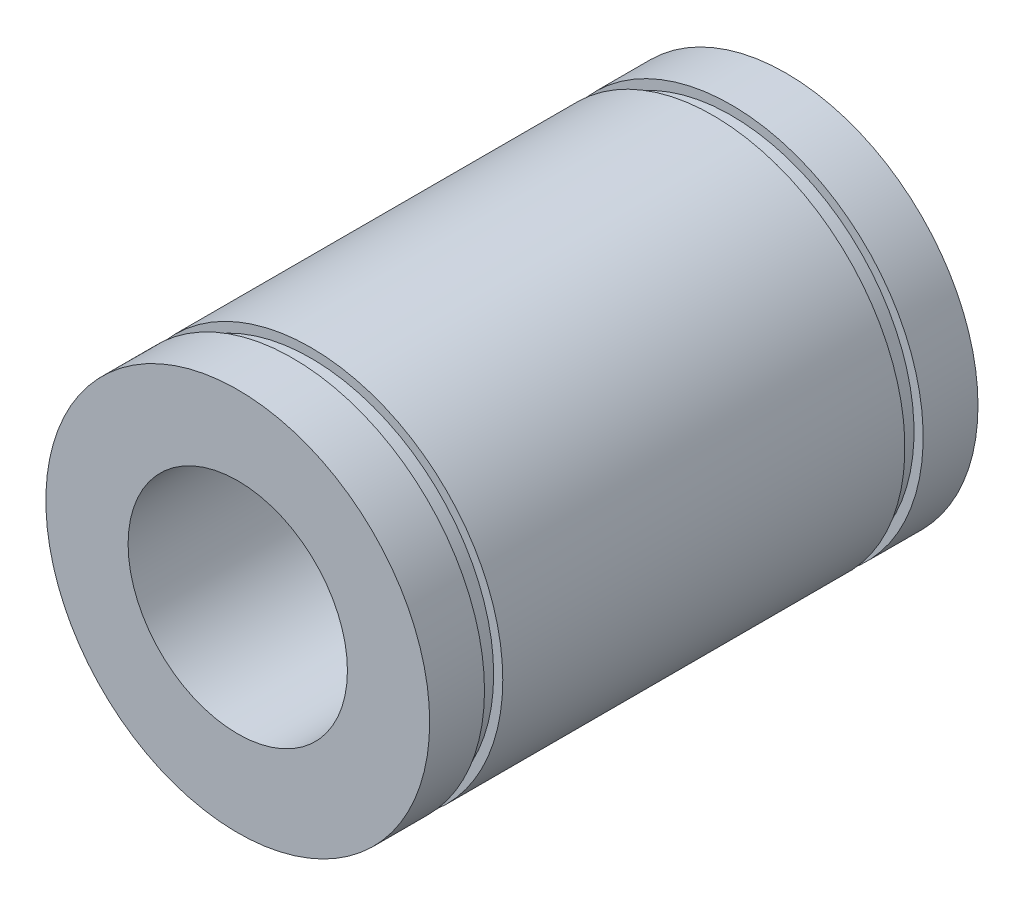
SolidWorks part; units mm, degrees
ref_plane "Front Plane" through (0, 0, 0) normal (0, 0, 1) x (1, 0, 0)
ref_plane "Top Plane" through (0, 0, 0) normal (0, 1, 0) x (1, 0, 0)
ref_plane "Right Plane" through (0, 0, 0) normal (1, 0, 0) x (0, 0, -1)
sketch "Sketch1" plane through (0, 0, 0) normal (0, 0, 1) x (1, 0, 0)
  circle A0 centre (0, 0) radius 10.5
  dimension "D1" = 21
extrude "Boss-Extrude1" add sketch "Sketch1" along normal blind 30
sketch "Sketch2" plane through (0, 0, 0) normal (0, 0, -1) x (-1, 0, 0)
  circle A0 centre (0, 0.1882) radius 6
  dimension "D1" = 12
extrude "Cut-Extrude1" cut sketch "Sketch2" against normal blind 30
sketch "Sketch3" plane through (0, 0, 0) normal (0, 0, -1) x (-1, 0, 0)
  circle A0 centre (0, 0) radius 10.5
  circle A1 centre (0, 0) radius 10
  dimension "D1" = 21
  dimension "D2" = 0.5
extrude "Cut-Extrude2" cut sketch "Sketch3" against normal blind 1 from offset 3 offset against normal yes
sketch "Sketch4" plane through (0, 0, 30) normal (0, 0, 1) x (1, 0, 0)
  circle A0 centre (0, 0) radius 10.5
  circle A1 centre (0, 0) radius 10
  dimension "D1" = 21
  dimension "D2" = 0.5
extrude "Cut-Extrude3" cut sketch "Sketch4" against normal blind 1 from offset 3
